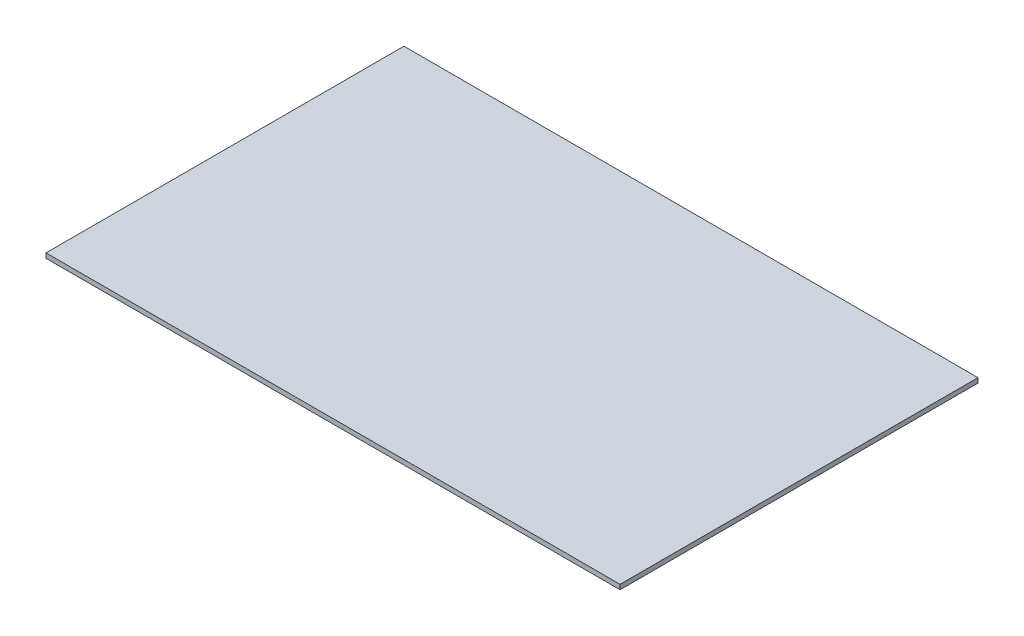
SolidWorks part; units mm, degrees
ref_plane "Front" through (0, 0, 0) normal (0, 0, 1) x (1, 0, 0)
ref_plane "Top" through (0, 0, 0) normal (0, 1, 0) x (1, 0, 0)
ref_plane "Right" through (0, 0, 0) normal (1, 0, 0) x (0, 0, -1)
sketch "Çizim3" plane through (0, 0, 0) normal (0, 1, 0) x (1, 0, 0)
  line L1 (-46.4304, 28.1667) -> (38.5696, 28.1667)
  line L2 (-46.4304, 28.1667) -> (-46.4304, -24.8333)
  line L3 (-46.4304, -24.8333) -> (38.5696, -24.8333)
  line L4 (38.5696, 28.1667) -> (38.5696, -24.8333)
  dimension "D1" = 85
  dimension "D2" = 53
extrude "Yükseklik-Ekstrüzyon1" add sketch "Çizim3" along normal blind 0.7
